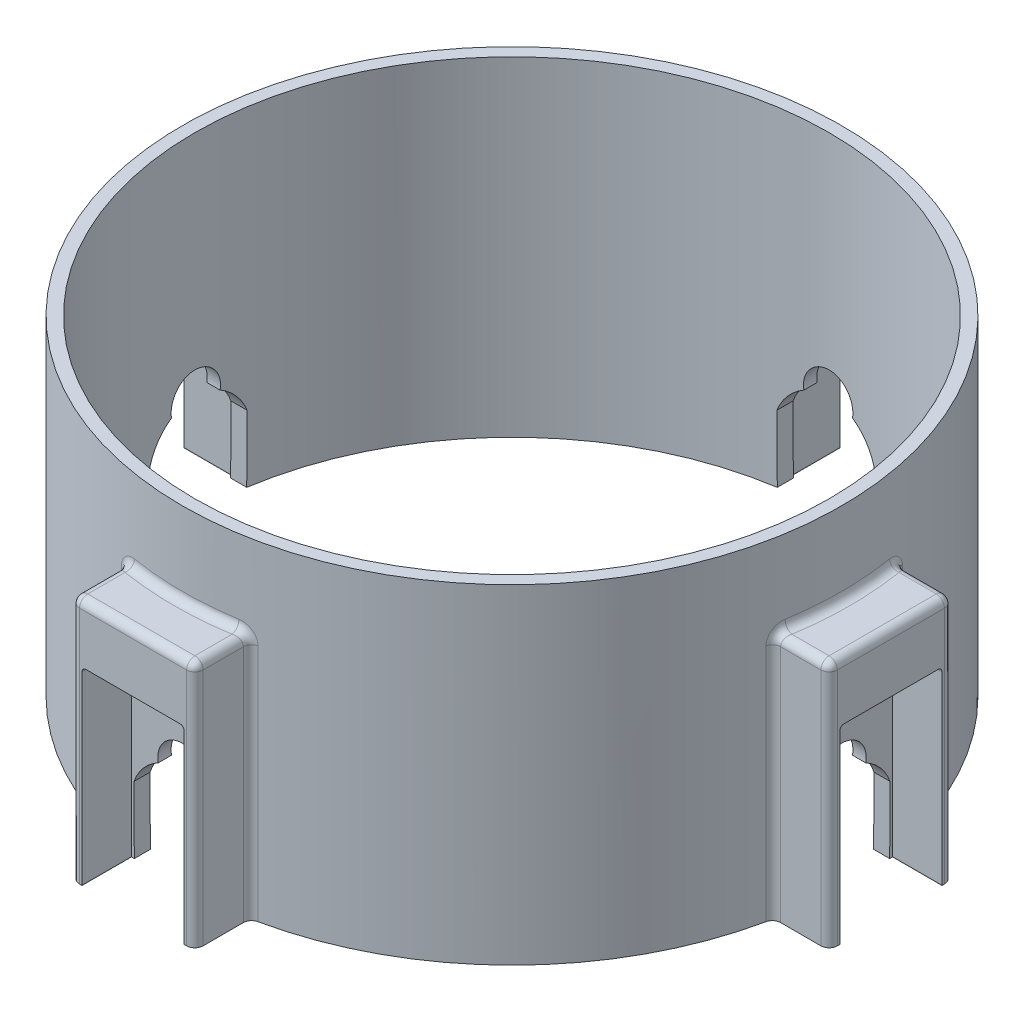
SolidWorks part; units mm, degrees
ref_plane "Front Plane" through (0, 0, 0) normal (0, 0, 1) x (1, 0, 0)
ref_plane "Top Plane" through (0, 0, 0) normal (0, 1, 0) x (1, 0, 0)
ref_plane "Right Plane" through (0, 0, 0) normal (1, 0, 0) x (0, 0, -1)
sketch "Sketch1" plane through (0, 0, 0) normal (0, 1, 0) x (1, 0, 0)
  circle A0 centre (0, 0) radius 40
  circle A1 centre (0, 0) radius 38.5
  dimension "D1" = 80
  dimension "D2" = 1.5
extrude "Boss-Extrude1" add sketch "Sketch1" along normal blind 40
ref_plane "Plane1" through (0, 0, 40) normal (0, 0, 1) x (1, 0, 0)
sketch "Sketch2" plane through (0, 0, 40) normal (0, 0, 1) x (1, 0, 0)
  line L0 (0, 0) -> (0, 45.4693) construction
  line L1 (-40, 0) -> (40, 0) construction
  line L2 (-7.5, 30) -> (7.5, 30)
  line L3 (-7.5, 30) -> (-7.5, 0)
  line L4 (-7.5, 0) -> (7.5, 0)
  line L5 (7.5, 30) -> (7.5, 0)
  line L6 (-7.5, 30) -> (7.5, 0) construction
  line L7 (-7.5, 0) -> (7.5, 30) construction
  point P3 (0, 15)
  dimension "D1" = 15
  dimension "D2" = 30
extrude "Boss-Extrude2" add sketch "Sketch2" along normal blind 6 and the other way up to surface
sketch "Sketch3" plane through (0, 0, 40) normal (0, 0, 1) x (1, 0, 0)
  line L0 (5.8884, 8.095) -> (5.8491, -0.1406)
  line L1 (-5.8884, 8.095) -> (-5.8491, -0.1406)
  line L2 (-5.8491, -0.1406) -> (5.8491, -0.1406)
  arc A18 (-2.9509, 11.5095) -> (-5.8884, 8.095) centre (0, 6) ccw
  arc A19 (2.9509, 11.5095) -> (-2.9509, 11.5095) centre (0, 12.05) ccw
  arc A20 (5.8884, 8.095) -> (2.9509, 11.5095) centre (0, 6) ccw
extrude "Cut-Extrude1" cut sketch "Sketch3" against normal blind 2
sketch "Sketch4" plane through (0, 0, 40) normal (0, 0, 1) x (1, 0, 0)
  line L45 (-5.7, -0.45) -> (5.7, -0.45)
  line L48 (6.2, 0.05) -> (6.2, 22.45)
  line L49 (5.7, 22.95) -> (-5.7, 22.95)
  line L50 (-6.2, 22.45) -> (-6.2, 0.05)
  arc A46 (-6.2, 0.05) -> (-5.7, -0.45) centre (-5.7, 0.05) ccw
  arc A47 (5.7, -0.45) -> (6.2, 0.05) centre (5.7, 0.05) ccw
  arc A48 (6.2, 22.45) -> (5.7, 22.95) centre (5.7, 22.45) ccw
  arc A49 (-5.7, 22.95) -> (-6.2, 22.45) centre (-5.7, 22.45) ccw
extrude "Cut-Extrude2" cut sketch "Sketch4" along normal through all
ref_plane "Plane2" through (0, 0, 41.5) normal (0, 0, 1) x (1, 0, 0)
sketch "Sketch5" plane through (0, 0, 41.5) normal (0, 0, 1) x (1, 0, 0)
  line L66 (-0.3, 25.966) -> (0.3, 25.966)
  line L75 (-5.7, 22.85) -> (-6.2, 22.85)
  line L76 (5.7, 22.85) -> (-5.7, 22.85)
  line L77 (6.2, 22.85) -> (5.7, 22.85)
  line L78 (6.2, 27.05) -> (6.2, 22.85)
  line L79 (0.8, 27.55) -> (5.7, 27.55)
  line L80 (0.3, 25.966) -> (0.3, 27.05)
  line L81 (-0.3, 27.05) -> (-0.3, 25.966)
  line L82 (-5.7, 27.55) -> (-0.8, 27.55)
  line L83 (-6.2, 22.85) -> (-6.2, 27.05)
  arc A42 (6.2, 27.05) -> (5.7, 27.55) centre (5.7, 27.05) ccw
  arc A43 (0.8, 27.55) -> (0.3, 27.05) centre (0.8, 27.05) ccw
  arc A44 (-0.3, 27.05) -> (-0.8, 27.55) centre (-0.8, 27.05) ccw
  arc A45 (-5.7, 27.55) -> (-6.2, 27.05) centre (-5.7, 27.05) ccw
extrude "Cut-Extrude3" cut sketch "Sketch5" along normal blind 3.1
fillet "Fillet1" radius 1 8 edges at (0, 30, 40) (7.5, 30, 42.6453) (7.5, 15, 46) (7.5, 15, 39.2906) (-7.5, 15, 39.2906) (-7.5, 30, 42.6453) (-7.5, 15, 46) (0, 30, 46)
pattern_circular "CirPattern1" count 4 over 360 about axis through (0, 0, 0) along (0, 1, 0) of "Boss-Extrude2", "Cut-Extrude1", "Cut-Extrude2", "Cut-Extrude3", "Fillet1"
